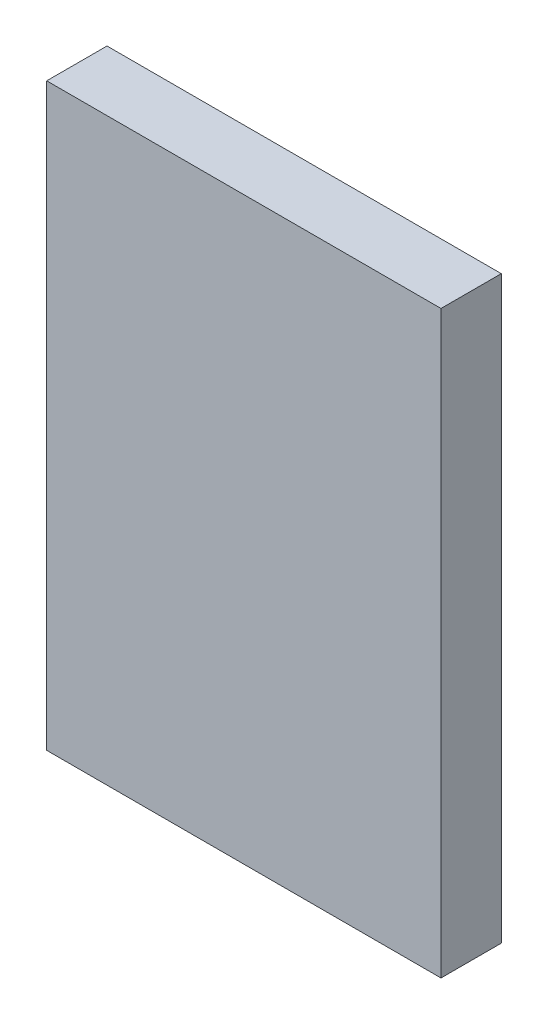
SolidWorks part; units mm, degrees
ref_plane "前视基准面" through (0, 0, 0) normal (0, 0, 1) x (1, 0, 0)
ref_plane "上视基准面" through (0, 0, 0) normal (0, 1, 0) x (1, 0, 0)
ref_plane "右视基准面" through (0, 0, 0) normal (1, 0, 0) x (0, 0, -1)
other "Configuration Table"
sketch "草图1" plane through (0, 0, 0) normal (0, 0, 1) x (1, 0, 0)
  line L1 (-11.1245, 34.36) -> (22.8755, 34.36)
  line L2 (-11.1245, 34.36) -> (-11.1245, -15.64)
  line L3 (-11.1245, -15.64) -> (22.8755, -15.64)
  line L4 (22.8755, 34.36) -> (22.8755, -15.64)
  line L5 (-11.1245, 34.36) -> (22.8755, -15.64) construction
  line L6 (-11.1245, -15.64) -> (22.8755, 34.36) construction
  point P0 (5.8755, 9.36)
  dimension "D1" = 50
  dimension "D2" = 34
extrude "凸台-拉伸1" add sketch "草图1" along normal blind 5.2
